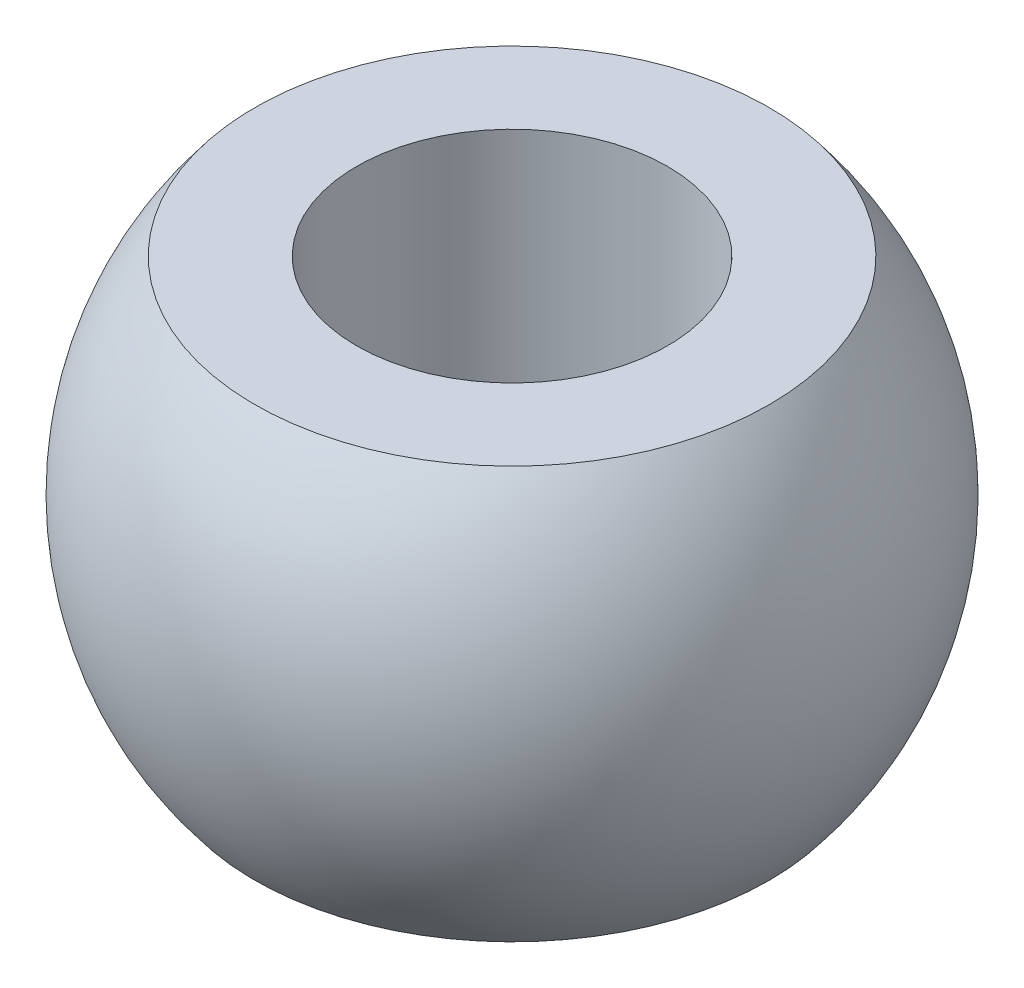
SolidWorks part; units mm, degrees
ref_plane "Front Plane" through (0, 0, 0) normal (0, 0, 1) x (1, 0, 0)
ref_plane "Top Plane" through (0, 0, 0) normal (0, 1, 0) x (1, 0, 0)
ref_plane "Right Plane" through (0, 0, 0) normal (1, 0, 0) x (0, 0, -1)
sketch "Sketch1" plane through (0, 0, 0) normal (0, 0, 1) x (1, 0, 0)
  line L0 (5, 6.625) -> (8.2746, 6.625)
  line L4 (5, 6.625) -> (5, -6.625)
  line L5 (0, 0) -> (5, -6.625) construction
  line L6 (0, 0) -> (5, 6.625) construction
  line L9 (5, -6.625) -> (8.2746, -6.625)
  line L10 (0, 6.625) -> (0, -6.625) construction
  arc A1 (8.2746, -6.625) -> (8.2746, 6.625) centre (0, 0) ccw
  point P0 (0, 0)
  dimension "D3" = 10.6
  dimension "D1" = 5
  dimension "D2" = 13.25
revolve "Revolve2" add sketch "Sketch1" angle 360 about L10
equation "\"shaft inner diameter\"= 15mm "
equation "\"shaft outer diameter\"= 20mm "
equation "\"column angle\" = 45deg "
equation "\"keyway_height\" = 1.39mm "
equation "\"keyway_width\" = 2.78mm "
equation "\"keyway_length\" = 30mm "
equation "\"steering column length\" = 555mm "
equation "\"steering wheel bolt width\" = 6mm "
equation "\"steering wheel bolt length\" = 40mm "
equation "\"bushing length\" = 40mm "
equation "\"bushing thickness\" = 3mm "
equation "\"u_joint clearance\" = 30mm "
equation "\"u_joint thickness\" = 7.5mm "
equation "\"horizontal shaft length\" = 90mm "
equation "\"short_bearing_outer_width\" = 10mm "
equation "\"column bushing diameter\" = \"primary shaft small diameter\" + 4 "
equation "\"column bushing distance\" = \"steering column length\"/4 "
equation "\"pinion width\" = 26.5mm "
equation "\"pin hole diameter\" = 10mm "
equation "\"rack hole to hole\" = 500mm "
equation "\"rack length\" = \"rack hole to hole\" + \"pin hole diameter\"*2 "
equation "\"pitch diameter\" = \"max travel\"/(pi * \"turn to lock\") "
equation "\"number of teeth\" = 18mm "
equation "\"module\" = \"pitch diameter\" / \"number of teeth\" "
equation "\"pressure angle\" = 20deg "
equation "\"D1@Sketch1\"=\"pin hole diameter\"/2"
equation "\"D2@Sketch1\"=\"pinion width\"/2"
equation "\"wheel base\" = 1561mm "
equation "\"track\" = 1354mm "
equation "\"turning radius\" = 2000mm "
equation "\"steering arm length\" = 100mm "
equation "\"turn to lock\" = 0.75mm "
equation "\"D3@Sketch1\"=\"pinion width\"/2.5"
equation "\"max turning angle\" = atn(\"wheel base\" / (\"turning radius\" - 0.5 * \"track\")) "
equation "\"max travel\" = 2 * \"steering arm length\" * sin(0.5 * \"max turning angle\") "
equation "\"primary shaft small diameter\" = 16mm "
equation "\"primary shaft large diameter\" = 24mm "
equation "\"secondary shaft small diameter\" = 16mm "
equation "\"secondary shaft large diameter\" = 25mm "
equation "\"tie rod length\" = 305mm "
equation "\"tie rod inner diameter\" = 6.6mm "
equation "\"tie rod outer diameter\" = 8.1mm "
equation "\"rack height\" = \"pin hole diameter\" * 2mm"
